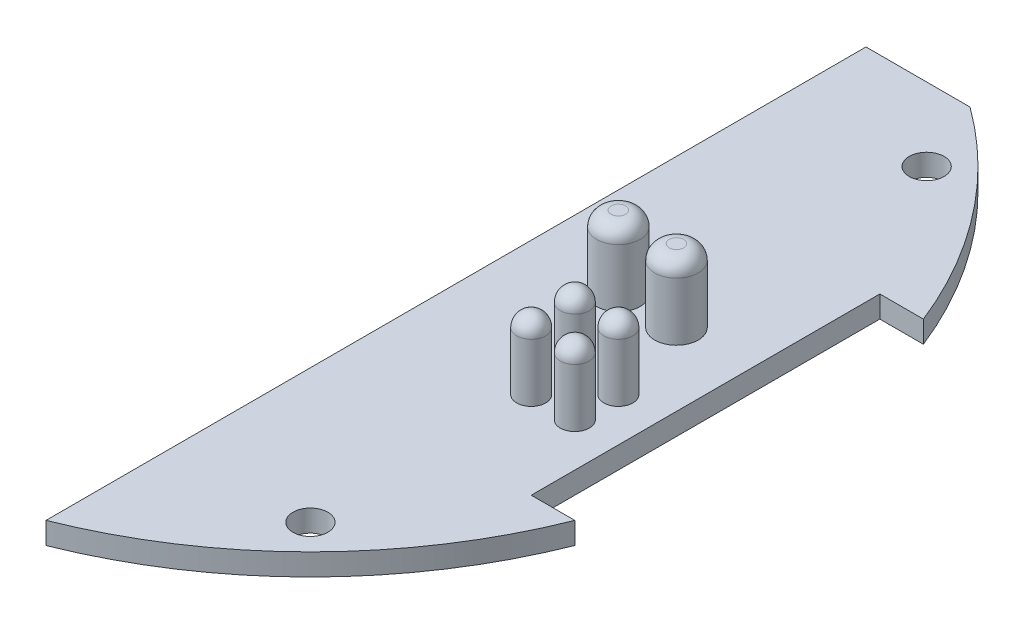
SolidWorks part; units mm, degrees
ref_plane "前视基准面" through (0, 0, 0) normal (0, 0, 1) x (1, 0, 0)
ref_plane "上视基准面" through (0, 0, 0) normal (0, 1, 0) x (1, 0, 0)
ref_plane "右视基准面" through (0, 0, 0) normal (1, 0, 0) x (0, 0, -1)
other "Configuration Table"
sketch "草图1" plane through (0, 0, 0) normal (0, 1, 0) x (1, 0, 0)
  circle A0 centre (0, 0) radius 32.5
  circle A1 centre (0, 0) radius 30 construction
  circle A3 centre (21.2132, 21.2132) radius 1.2
  circle A5 centre (21.2132, -21.2132) radius 1.2
  circle A7 centre (-21.2132, -21.2132) radius 1.2
  circle A9 centre (-21.2132, 21.2132) radius 1.2
  point P15 (0, 0)
  dimension "D1" = 65
  dimension "D2" = 60
extrude "凸台-拉伸1" add sketch "草图1" along normal blind 1.5
sketch "草图2" plane through (0, 1.5, 0) normal (0, 1, 0) x (1, 0, 0)
  line L0 (34.4418, 0) -> (-43.9173, 0) construction
  line L1 (30.2035, 12) -> (27.2035, 12)
  line L2 (27.2035, 12) -> (27.2035, -12)
  line L3 (30.2035, -12) -> (27.2035, -12)
  line L4 (0, 22.8929) -> (0, -32.5) construction
  line L8 (12, -27.2035) -> (-12, -27.2035)
  line L9 (-12, -30.2035) -> (-12, -27.2035)
  line L10 (12, -30.2035) -> (12, -27.2035)
  line L11 (-27.2035, -12) -> (-27.2035, 12)
  line L12 (-30.2035, 12) -> (-27.2035, 12)
  line L13 (-30.2035, -12) -> (-27.2035, -12)
  line L14 (-12, 27.2035) -> (12, 27.2035)
  line L15 (12, 30.2035) -> (12, 27.2035)
  line L16 (-12, 30.2035) -> (-12, 27.2035)
  circle A0 centre (0, 0) radius 32.5 construction
  arc A1 (30.2035, -12) -> (30.2035, 12) centre (0, 0) ccw
  arc A3 (-12, -30.2035) -> (12, -30.2035) centre (0, 0) ccw
  arc A4 (-30.2035, 12) -> (-30.2035, -12) centre (0, 0) ccw
  arc A5 (12, 30.2035) -> (-12, 30.2035) centre (0, 0) ccw
  point P9 (27.2035, 0)
  point P27 (0, 0)
  dimension "D1" = 12
  dimension "D2" = 3
  dimension "D3" = 4
extrude "切除-拉伸1" cut sketch "草图2" against normal through all
sketch "草图3" plane through (0, 1.5, 0) normal (0, 1, 0) x (1, 0, 0)
  line L1 (17, 26.25) -> (-17, 26.25)
  line L2 (17, 26.25) -> (28.1494, 26.25)
  line L3 (28.1494, 26.25) -> (-14.2404, 46.7454)
  line L4 (-14.2404, 46.7454) -> (-27.1497, 26.25)
  line L5 (-27.1497, 26.25) -> (-17, 26.25)
extrude "切除-拉伸2" cut sketch "草图3" against normal through all
sketch "草图4" plane through (0, 1.5, 0) normal (0, 1, 0) x (1, 0, 0)
  circle A0 centre (22.2035, 3) radius 1.5 construction
  circle A1 centre (22.2035, 3) radius 1.5
  circle A2 centre (18.2035, 3) radius 1.5 construction
  circle A3 centre (18.2035, 3) radius 1.5
  circle A4 centre (24.2035, -6) radius 1 construction
  circle A5 centre (24.2035, -6) radius 1
  circle A6 centre (24.2035, -3) radius 1 construction
  circle A7 centre (24.2035, -3) radius 1
  circle A8 centre (21.2035, -6) radius 1 construction
  circle A9 centre (21.2035, -6) radius 1
  circle A10 centre (21.2035, -3) radius 1 construction
  circle A11 centre (21.2035, -3) radius 1
extrude "凸台-拉伸2" add sketch "草图4" along normal blind 5
fillet "圆角1" radius 1 6 edges at (21.2035, 6.5, 7) (18.2035, 6.5, -1.5) (21.2035, 6.5, 4) (24.2035, 6.5, 7) (24.2035, 6.5, 4) (22.2035, 6.5, -1.5)
sketch "草图5" plane through (0, 1.5, 0) normal (0, 1, 0) x (1, 0, 0)
  line L0 (12, -30.2035) -> (12, 30.7441)
  line L1 (12, -30.2035) -> (12, -27.2035) construction
  line L2 (12, 30.7441) -> (-38.713, 30.7441)
  line L3 (-38.713, 30.7441) -> (-38.713, -27.2035)
  line L4 (-38.713, -27.2035) -> (12, -30.2035)
extrude "切除-拉伸3" cut sketch "草图5" against normal blind 5
